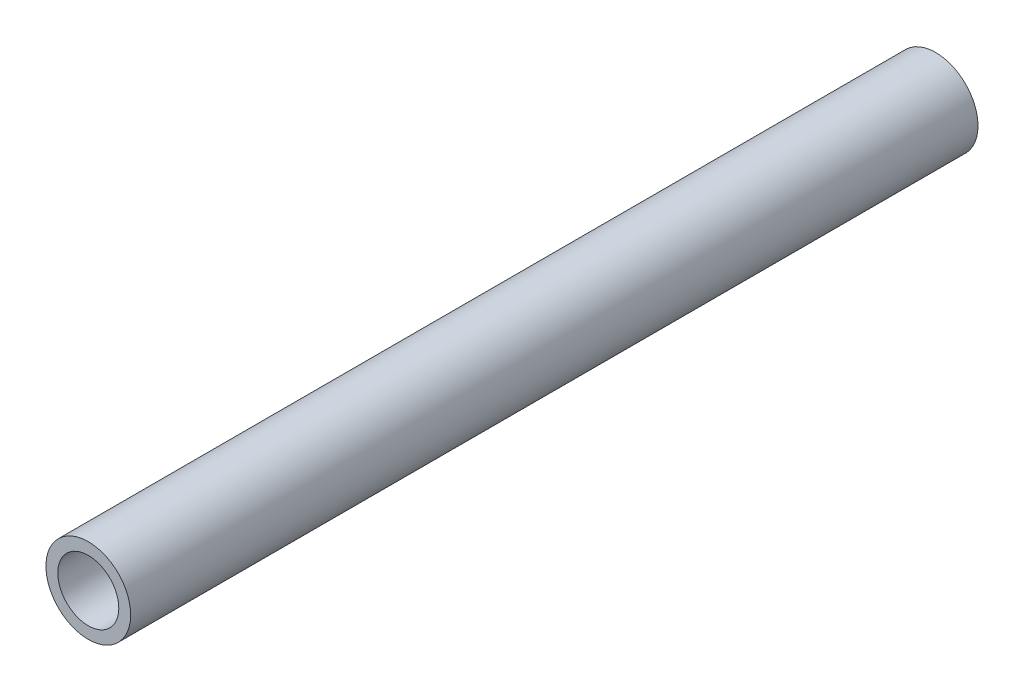
SolidWorks part; units mm, degrees
ref_plane "Front" through (0, 0, 0) normal (0, 0, 1) x (1, 0, 0)
ref_plane "Top" through (0, 0, 0) normal (0, 1, 0) x (1, 0, 0)
ref_plane "Right" through (0, 0, 0) normal (1, 0, 0) x (0, 0, -1)
sketch "Sketch1" plane through (0, 0, 0) normal (0, 0, 1) x (1, 0, 0)
  line L0 (-3.175, 0) -> (3.175, 0) construction
  line L1 (0, -3.175) -> (0, 3.175) construction
  circle A0 centre (0, 0) radius 3.175
  circle A1 centre (0, 0) radius 2.286
  point P4 (0, 0)
  point P8 (0, 0)
  point P9 (2.286, 0)
  dimension "D3" = 4.572
  dimension "D1" = 6.35
  dimension "D2" = 0.889
extrude "Boss-Extrude1" add sketch "Sketch1" along normal blind 63.5
